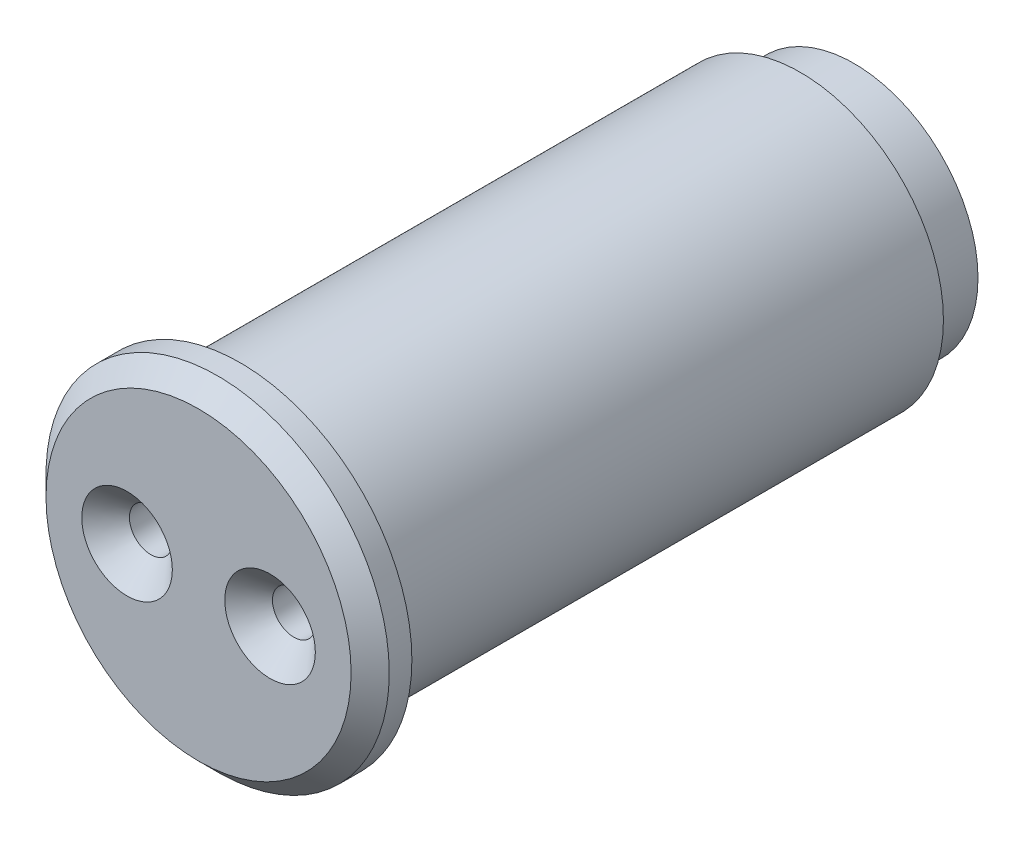
SolidWorks part; units mm, degrees
ref_plane "前视基准面" through (0, 0, 0) normal (0, 0, 1) x (1, 0, 0)
ref_plane "上视基准面" through (0, 0, 0) normal (0, 1, 0) x (1, 0, 0)
ref_plane "右视基准面" through (0, 0, 0) normal (1, 0, 0) x (0, 0, -1)
sketch "草图1" plane through (0, 0, 0) normal (0, 0, 1) x (1, 0, 0)
  circle A0 centre (0, 0) radius 5.2
extrude "凸台-拉伸1" add sketch "草图1" along normal blind 27.5
ref_plane "基准面4" through (0, 0, 13.75) normal (0, 0, 1) x (1, 0, 0)
sketch "草图3" plane through (0, 0, 27.5) normal (0, 0, 1) x (1, 0, 0)
  line L0 (0, 0) -> (0, 5.6384) construction
  circle A0 centre (-3, 0) radius 0.85
  circle A1 centre (3, 0) radius 0.85
  point P9 (0, 0)
  dimension "D1" = 1.7
  dimension "D2" = 3
  dimension "D3" = 2
sketch "草图6" plane through (0, 0, 27.5) normal (0, 0, 1) x (1, 0, 0)
  circle A0 centre (0, 0) radius 7.2
extrude "凸台-拉伸3" add sketch "草图6" against normal blind 1.75
sketch "草图8" plane through (0, 0, 25.75) normal (0, 0, -1) x (-1, 0, 0)
  circle A1 centre (0, 0) radius 6
extrude "凸台-拉伸4" add sketch "草图8" along normal blind 23.5
extrude "切除-拉伸4" cut sketch "草图3" against normal blind 8
mirror "镜向3" about plane through (0, 0, 13.75) normal (0, 0, 1) of "切除-拉伸4"
sketch "草图7" plane through (0, 0, 27.5) normal (0, 0, 1) x (1, 0, 0)
  circle A0 centre (-3, 0) radius 0.9
  circle A1 centre (3, 0) radius 0.9
extrude "切除-拉伸5" cut sketch "草图7" against normal up to surface (8 mm away) up to face at (-2.15, 0, 19.5)
chamfer "倒角1" distance 1 angle 45 2 edges at (-2.15, 0, 0) (3.85, 0, 0)
chamfer "倒角2" distance 1 angle 45 2 edges at (-2.1, 0, 27.5) (3.9, 0, 27.5)
sketch "草图9" plane through (0, 0, 0) normal (0, 0, -1) x (-1, 0, 0)
  line L0 (0, 0) -> (-0.0918, 7.7012) construction
  line L1 (0, 0) -> (10.2592, 0.1223) construction
  circle A0 centre (-1.6006, 2.9519) radius 0.4939
  circle A1 centre (1.5297, 2.9893) radius 0.4939
  circle A2 centre (1.6006, -2.9519) radius 0.4939
  circle A3 centre (-1.5297, -2.9893) radius 0.4939
extrude "切除-拉伸6" cut sketch "草图9" against normal blind 1
chamfer "倒角3" distance 0.8 angle 45 1 edges at (7.2, 0, 27.5)
